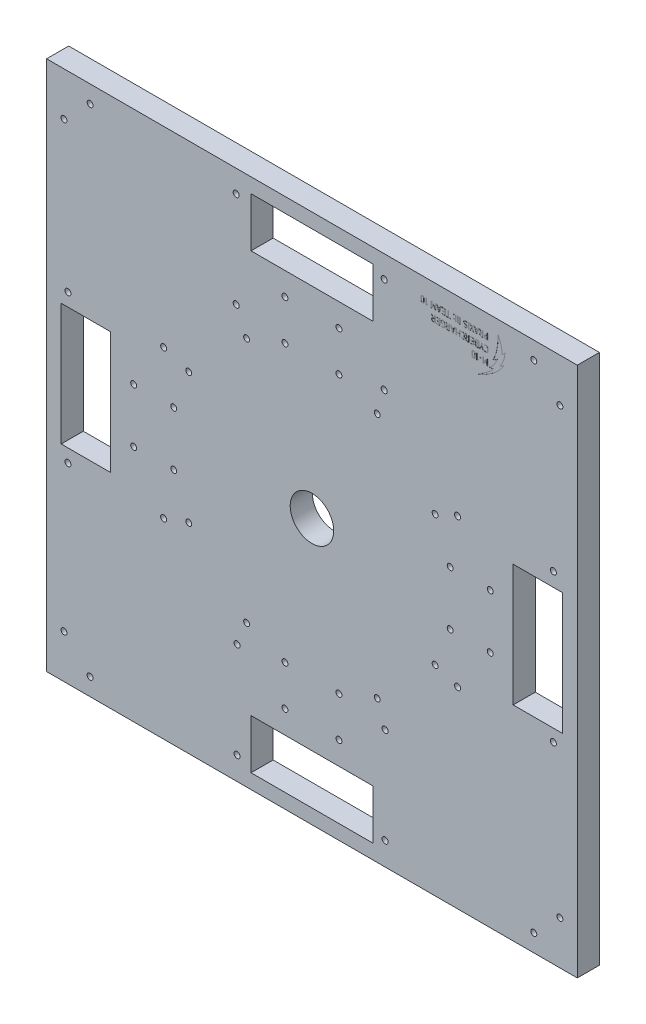
SolidWorks part; units mm, degrees
material "Balsa"
ref_plane "Front Plane" through (0, 0, 0) normal (0, 0, 1) x (1, 0, 0)
ref_plane "Top Plane" through (0, 0, 0) normal (0, 1, 0) x (1, 0, 0)
ref_plane "Right Plane" through (0, 0, 0) normal (1, 0, 0) x (0, 0, -1)
sketch "Sketch2" plane through (0, 0, 0) normal (0, 0, 1) x (1, 0, 0)
  line L1 (0, 0) -> (304.8, 0)
  line L2 (0, 0) -> (0, 304.8)
  line L3 (0, 304.8) -> (304.8, 304.8)
  line L4 (304.8, 0) -> (304.8, 304.8)
extrude "1/2 MDF" add sketch "Sketch2" along normal blind 12.7
sketch "Sketch3" plane through (0, 0, 0) normal (0, 0, -1) x (-1, 0, 0)
  circle A0 centre (-152.4, 152.4) radius 12.5
  point P0 (-152.4, 152.4)
extrude "Center Wiring Hole" cut sketch "Sketch3" against normal blind 48
sketch "Sketch4" plane through (0, 0, 12.7) normal (0, 0, 1) x (1, 0, 0)
  line L0 (267.9631, 304.7908) -> (267.9631, 290.9523) construction
  line L1 (267.9631, 290.9523) -> (198.4481, 290.9523) construction
  line L14 (117.4, 267.9631) -> (187.4, 267.9631)
  line L17 (155.8742, 271.6042) -> (155.8742, 267.9631)
  line L20 (117.4, 267.9631) -> (187.4, 267.9631)
  line L22 (296.4163, 152.4) -> (296.4163, 187.4)
  line L23 (296.4163, 187.4) -> (267.9631, 187.4)
  line L24 (296.4163, 187.4) -> (296.4163, 117.4)
  line L25 (296.4163, 117.4) -> (267.9631, 117.4)
  line L26 (267.9631, 187.4) -> (267.9631, 117.4)
  line L27 (152.4, 8.3837) -> (187.4, 8.3837)
  line L28 (187.4, 8.3837) -> (187.4, 36.8369)
  line L29 (187.4, 8.3837) -> (117.4, 8.3837)
  line L30 (117.4, 8.3837) -> (117.4, 36.8369)
  line L31 (187.4, 36.8369) -> (117.4, 36.8369)
  line L32 (8.3837, 152.4) -> (8.3837, 117.4)
  line L33 (8.3837, 117.4) -> (36.8369, 117.4)
  line L34 (8.3837, 117.4) -> (8.3837, 187.4)
  line L35 (8.3837, 187.4) -> (36.8369, 187.4)
  line L36 (36.8369, 117.4) -> (36.8369, 187.4)
  line L37 (117.4, 267.9631) -> (117.4, 296.4163)
  line L38 (117.4, 296.4163) -> (187.4, 296.4163)
  line L39 (187.4, 267.9631) -> (187.4, 296.4163)
  circle A0 centre (136.9, 254.7804) radius 1.7
  circle A1 centre (167.9, 254.7804) radius 1.7
  circle A2 centre (136.9, 231.7812) radius 1.7
  circle A3 centre (167.9, 231.7812) radius 1.7
  circle A36 centre (189.9, 81.65) radius 1.7 construction
  circle A37 centre (114.9, 81.65) radius 1.7 construction
  circle A38 centre (114.9, 223.15) radius 1.7 construction
  circle A39 centre (189.9, 223.15) radius 1.7 construction
  circle A44 centre (25, 294.8) radius 1.7
  circle A45 centre (10, 279.8) radius 1.7
  circle A46 centre (114.9, 223.15) radius 1.7
  circle A47 centre (189.9, 223.15) radius 1.7
  circle A48 centre (189.9, 81.65) radius 1.7
  circle A49 centre (114.9, 81.65) radius 1.7
  circle A60 centre (136.9, 254.7804) radius 1.7 construction
  circle A61 centre (136.9, 231.7812) radius 1.7 construction
  circle A64 centre (167.9, 231.7812) radius 1.7 construction
  circle A65 centre (167.9, 254.7804) radius 1.7 construction
  circle A66 centre (294.8188, 279.8) radius 1.7
  circle A67 centre (279.8188, 294.8) radius 1.7
  circle A68 centre (254.7992, 167.9) radius 1.7
  circle A69 centre (231.8, 167.9) radius 1.7
  circle A70 centre (254.7992, 136.9) radius 1.7
  circle A71 centre (231.8, 136.9) radius 1.7
  circle A72 centre (279.8188, 9.9812) radius 1.7
  circle A73 centre (294.8188, 24.9812) radius 1.7
  circle A74 centre (167.9188, 50.0008) radius 1.7
  circle A75 centre (167.9188, 73) radius 1.7
  circle A76 centre (136.9188, 50.0008) radius 1.7
  circle A77 centre (136.9188, 73) radius 1.7
  circle A78 centre (10, 24.9812) radius 1.7
  circle A79 centre (25, 9.9812) radius 1.7
  circle A80 centre (50.0196, 136.8812) radius 1.7
  circle A81 centre (73.0188, 136.8812) radius 1.7
  circle A82 centre (50.0196, 167.8812) radius 1.7
  circle A83 centre (73.0188, 167.8812) radius 1.7
  circle A84 centre (81.65, 189.9) radius 1.7
  circle A85 centre (81.65, 114.9) radius 1.7
  circle A86 centre (189.9, 223.15) radius 1.7
  circle A87 centre (114.9, 223.15) radius 1.7
  circle A88 centre (223.15, 114.9) radius 1.7
  circle A89 centre (223.15, 189.9) radius 1.7
  text T0 "<b><i>Team 10</i></b>\r\n<b><i>Front Toward Enemy</i></b>"
  point P5 (189.9, 223.15)
  point P6 (189.9, 81.65)
  point P10 (114.9, 81.65)
  point P11 (114.9, 223.15)
  point P15 (25, 294.8)
  point P16 (10, 279.8)
  point P39 (152.4, 152.4)
  point P40 (152.4, 267.9631)
  point P72 (136.9, 231.7812)
  point P73 (167.9, 231.7812)
  point P74 (167.9, 254.7804)
  point P79 (136.9, 254.7804)
  point P92 (152.4094, 152.3906)
  point P105 (152.4, 152.4)
  point P355 (152.4, 152.4)
  point P365 (152.4, 152.4)
  dimension "D1" = 4
  dimension "D2" = 4
  dimension "D3" = 4
extrude "Stepper Motor Holes" cut sketch "Sketch4" against normal blind 138
sketch "Sketch5" plane through (0, 0, 12.7) normal (0, 0, 1) x (1, 0, 0)
  circle A0 centre (12.259, 194.9) radius 1.741 construction
  circle A1 centre (67.259, 194.9) radius 1.741 construction
  circle A2 centre (12.259, 109.9) radius 1.741 construction
  circle A3 centre (67.259, 109.9) radius 1.741 construction
  circle A4 centre (12.259, 194.9) radius 1.741
  circle A5 centre (67.259, 194.9) radius 1.741
  circle A6 centre (12.259, 109.9) radius 1.741
  circle A7 centre (67.259, 109.9) radius 1.741
  circle A8 centre (152.4, 152.4) radius 12.5 construction
  circle A9 centre (152.4, 152.4) radius 12.5
  circle A10 centre (193.9, 237.05) radius 1.741
  circle A11 centre (193.9, 292.05) radius 1.741
  circle A12 centre (108.9, 292.05) radius 1.741
  circle A13 centre (108.9, 237.05) radius 1.741
  circle A14 centre (236.05, 110.409) radius 1.741
  circle A15 centre (291.05, 110.409) radius 1.741
  circle A16 centre (291.05, 195.409) radius 1.741
  circle A17 centre (236.05, 195.409) radius 1.741
  circle A18 centre (109.409, 68.259) radius 1.741
  circle A19 centre (109.409, 13.259) radius 1.741
  circle A20 centre (194.409, 13.259) radius 1.741
  circle A21 centre (194.409, 68.259) radius 1.741
  point P17 (12.259, 194.9)
  point P18 (12.259, 109.9)
  point P19 (67.259, 109.9)
  point P20 (67.259, 194.9)
  point P50 (151.6545, 152.6545)
  dimension "D2" = 4
extrude "Cut-Extrude2" cut sketch "Sketch5" against normal blind 185
sketch "Sketch6" plane through (0, 0, 12.7) normal (0, 0, 1) x (1, 0, 0)
  line L0 (253.8502, 304.8) -> (253.8502, 282.0779) construction
  line L1 (304.8, 304.8) -> (0, 304.8) construction
  line L2 (253.8502, 282.0779) -> (204.75, 282.0779) construction
  line L3 (510.4048, 503.9774) -> (177.0715, 503.9774) construction
  line L4 (259.1263, 297.6276) -> (259.5292, 293.0743) construction
  line L5 (259.5292, 293.0743) -> (258.8269, 288.7666) construction
  line L6 (258.8269, 288.7666) -> (257.4396, 284.7032) construction
  line L7 (257.4396, 284.7032) -> (256.3481, 283.3781) construction
  line L8 (259.1263, 297.6276) -> (261.2274, 293.5592) construction
  line L9 (261.2274, 293.5592) -> (261.7389, 289.6063) construction
  line L10 (261.7389, 289.6063) -> (261.5327, 288.481) construction
  line L11 (261.5327, 288.481) -> (262.634, 289.1692) construction
  line L12 (262.634, 289.1692) -> (263.2898, 290.3072) construction
  line L13 (263.2898, 290.3072) -> (262.9964, 285.9577) construction
  line L14 (262.9964, 285.9577) -> (261.566, 283.7035) construction
  line L15 (261.566, 283.7035) -> (260.2517, 282.2292) construction
  line L16 (260.2517, 282.2292) -> (261.6317, 282.4542) construction
  line L17 (261.6317, 282.4542) -> (262.8156, 283.6695) construction
  line L18 (262.8156, 283.6695) -> (259.3593, 278.0957) construction
  line L19 (259.3593, 278.0957) -> (255.6414, 275.6962) construction
  line L20 (255.6414, 275.6962) -> (250.7231, 272.7464) construction
  line L21 (250.7231, 272.7464) -> (246.6737, 271.3235) construction
  line L22 (246.6737, 271.3235) -> (250.3674, 273.3565) construction
  line L23 (250.3674, 273.3565) -> (254.0191, 275.7854) construction
  line L24 (254.0191, 275.7854) -> (256.1095, 277.9752) construction
  line L25 (256.1095, 277.9752) -> (256.8902, 279.188) construction
  line L26 (256.8902, 279.188) -> (255.6313, 278.5051) construction
  line L27 (255.6313, 278.5051) -> (254.7721, 278.5051) construction
  line L28 (254.7721, 278.5051) -> (254.3269, 278.6199) construction
  line L29 (254.3269, 278.6199) -> (256.6138, 280.0928) construction
  line L30 (256.6138, 280.0928) -> (258.165, 282.611) construction
  line L31 (258.165, 282.611) -> (258.8225, 284.8028) construction
  line L32 (258.8225, 284.8028) -> (257.458, 283.576) construction
  line L33 (257.458, 283.576) -> (256.3481, 283.3781) construction
  spline S0 degree 4 poles (259.1263, 297.6276) (259.5292, 293.0743) (258.8269, 288.7666) (257.4396, 284.7032) (256.3481, 283.3781) knots 0 0 0 0 0 1 1 1 1 1
  spline S1 degree 3 poles (259.1263, 297.6276) (261.2274, 293.5592) (261.7389, 289.6063) (261.5327, 288.481) knots 0 0 0 0 1 1 1 1
  spline S2 degree 2 poles (261.5327, 288.481) (262.634, 289.1692) (263.2898, 290.3072) knots 0 0 0 1 1 1
  spline S3 degree 3 poles (263.2898, 290.3072) (262.9964, 285.9577) (261.566, 283.7035) (260.2517, 282.2292) knots 0 0 0 0 1 1 1 1
  spline S4 degree 2 poles (260.2517, 282.2292) (261.6317, 282.4542) (262.8156, 283.6695) knots 0 0 0 1 1 1
  spline S5 degree 4 poles (262.8156, 283.6695) (259.3593, 278.0957) (255.6414, 275.6962) (250.7231, 272.7464) (246.6737, 271.3235) knots 0 0 0 0 0 1 1 1 1 1
  spline S6 degree 4 poles (246.6737, 271.3235) (250.3674, 273.3565) (254.0191, 275.7854) (256.1095, 277.9752) (256.8902, 279.188) knots 0 0 0 0 0 1 1 1 1 1
  spline S7 degree 3 poles (256.8902, 279.188) (255.6313, 278.5051) (254.7721, 278.5051) (254.3269, 278.6199) knots 0 0 0 0 1 1 1 1
  spline S8 degree 3 poles (254.3269, 278.6199) (256.6138, 280.0928) (258.165, 282.611) (258.8225, 284.8028) knots 0 0 0 0 1 1 1 1
  spline S9 degree 2 poles (258.8225, 284.8028) (257.458, 283.576) (256.3481, 283.3781) knots 0 0 0 1 1 1
  text T0 "M-10\r\nCYBERCHARGER\r\nPRAXIS III: TEAM 10\r\n"
  point P6 (256.3481, 283.3781)
  point P7 (259.1263, 297.6276)
  point P8 (261.5327, 288.481)
  point P11 (263.2898, 290.3072)
  point P12 (260.2517, 282.2292)
  point P13 (262.8156, 283.6695)
  point P14 (254.3269, 278.6199)
  point P15 (246.6737, 271.3235)
extrude "Cut-Extrude3" cut sketch "Sketch6" against normal blind 0.05
sketch "Sketch7" plane through (0, 0, 12.7) normal (0, 0, 1) x (1, 0, 0)
  line L2 (117.4, 296.4163) -> (187.4, 296.4163) construction
  line L3 (187.4, 267.9631) -> (187.4, 296.4163) construction
  line L4 (117.4, 267.9631) -> (187.4, 267.9631) construction
  line L5 (117.4, 267.9631) -> (117.4, 296.4163) construction
  line L6 (267.9631, 187.4) -> (267.9631, 117.4)
  line L7 (296.4163, 187.4) -> (267.9631, 187.4)
  line L12 (296.4163, 117.4) -> (296.4163, 187.4)
  line L13 (267.9631, 117.4) -> (296.4163, 117.4)
  line L14 (267.9631, 187.4) -> (267.9631, 117.4)
  line L15 (296.4163, 187.4) -> (267.9631, 187.4)
  line L16 (296.4163, 117.4) -> (296.4163, 187.4)
  line L17 (267.9631, 117.4) -> (296.4163, 117.4)
  line L18 (117.4, 296.4163) -> (187.4, 296.4163)
  line L19 (187.4, 267.9631) -> (187.4, 296.4163)
  line L20 (117.4, 267.9631) -> (187.4, 267.9631)
  line L21 (117.4, 267.9631) -> (117.4, 296.4163)
  line L22 (8.3837, 187.4) -> (36.8369, 187.4) construction
  line L23 (36.8369, 117.4) -> (36.8369, 187.4) construction
  line L24 (8.3837, 117.4) -> (36.8369, 117.4) construction
  line L25 (8.3837, 117.4) -> (8.3837, 187.4) construction
  line L26 (8.3837, 187.4) -> (36.8369, 187.4)
  line L27 (36.8369, 117.4) -> (36.8369, 187.4)
  line L28 (8.3837, 117.4) -> (36.8369, 117.4)
  line L29 (8.3837, 117.4) -> (8.3837, 187.4)
  line L34 (187.4, 36.8369) -> (117.4, 36.8369)
  line L35 (187.4, 8.3837) -> (187.4, 36.8369)
  line L36 (117.4, 8.3837) -> (187.4, 8.3837)
  line L37 (117.4, 36.8369) -> (117.4, 8.3837)
  line L38 (187.4, 36.8369) -> (117.4, 36.8369)
  line L39 (187.4, 8.3837) -> (187.4, 36.8369)
  line L40 (117.4, 8.3837) -> (187.4, 8.3837)
  line L41 (117.4, 36.8369) -> (117.4, 8.3837)
  line L42 (0, 304.8) -> (0, 0)
  line L43 (0, 0) -> (304.8, 0)
  line L44 (304.8, 0) -> (304.8, 304.8)
  line L45 (304.8, 304.8) -> (0, 304.8)
  line L50 (0, 304.8) -> (0, 0)
  line L51 (0, 0) -> (304.8, 0)
  line L52 (304.8, 0) -> (304.8, 304.8)
  line L53 (304.8, 304.8) -> (0, 304.8)
  circle A0 centre (152.4, 152.4) radius 12.5 construction
  circle A1 centre (152.4, 152.4) radius 12.5
  circle A2 centre (10, 279.8) radius 1.7 construction
  circle A3 centre (10, 279.8) radius 1.7
  circle A4 centre (25, 294.8) radius 1.7 construction
  circle A5 centre (25, 294.8) radius 1.7
  circle A6 centre (279.8188, 294.8) radius 1.7 construction
  circle A7 centre (294.8188, 279.8) radius 1.7 construction
  circle A8 centre (279.8188, 294.8) radius 1.7
  circle A9 centre (294.8188, 279.8) radius 1.7
  circle A10 centre (294.8188, 24.9812) radius 1.7 construction
  circle A11 centre (279.8188, 9.9812) radius 1.7 construction
  circle A12 centre (294.8188, 24.9812) radius 1.7
  circle A13 centre (279.8188, 9.9812) radius 1.7
  circle A14 centre (25, 9.9812) radius 1.7 construction
  circle A15 centre (10, 24.9812) radius 1.7 construction
  circle A16 centre (25, 9.9812) radius 1.7
  circle A17 centre (10, 24.9812) radius 1.7
  dimension "D1" = 0
  dimension "D2" = 0
  dimension "D3" = 0
